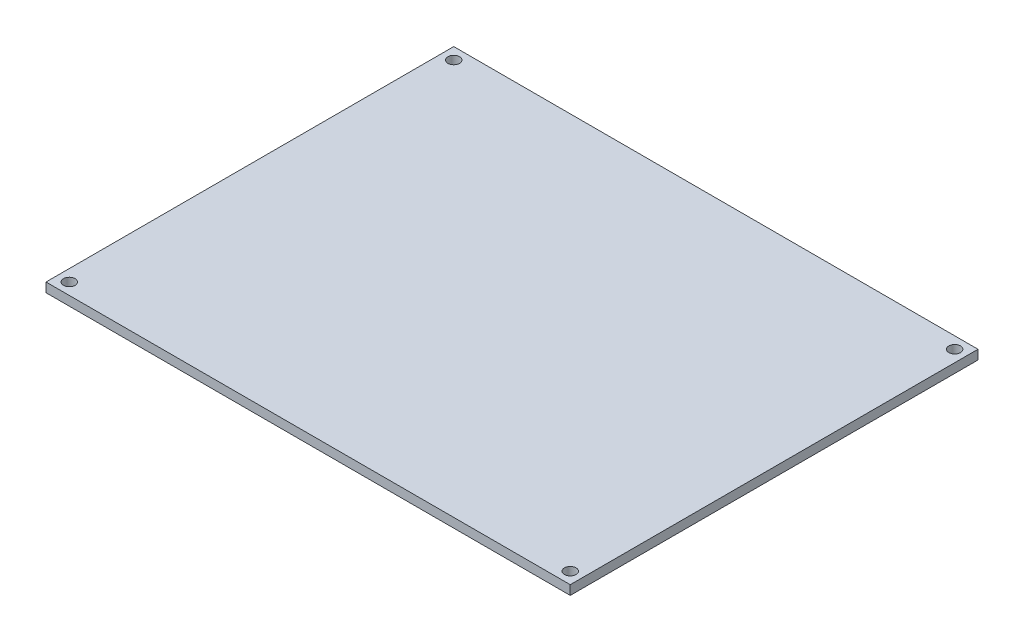
SolidWorks part; units mm, degrees
ref_plane "Front Plane" through (0, 0, 0) normal (0, 0, 1) x (1, 0, 0)
ref_plane "Top Plane" through (0, 0, 0) normal (0, 1, 0) x (1, 0, 0)
ref_plane "Right Plane" through (0, 0, 0) normal (1, 0, 0) x (0, 0, -1)
sketch "Sketch1" plane through (0, 0, 0) normal (0, 1, 0) x (1, 0, 0)
  line L5 (-45, -35) -> (45, -35)
  line L6 (-45, -35) -> (-45, 35)
  line L12 (-45, 35) -> (45, 35)
  line L13 (45, -35) -> (45, 35)
  line L14 (-45, -35) -> (45, 35) construction
  line L15 (-45, 35) -> (45, -35) construction
  line L16 (-43, -33) -> (43, -33) construction
  line L17 (-43, -33) -> (-43, 33) construction
  line L18 (-43, 33) -> (43, 33) construction
  line L19 (43, -33) -> (43, 33) construction
  line L20 (-43, -33) -> (43, 33) construction
  line L21 (-43, 33) -> (43, -33) construction
  circle A0 centre (-43, 33) radius 1
  circle A1 centre (43, 33) radius 1
  circle A2 centre (-43, -33) radius 1
  circle A3 centre (43, -33) radius 1
  point P0 (0, 0)
  point P6 (0, 0)
  dimension "D5" = 2
  dimension "D6" = 2
  dimension "D7" = 2
  dimension "D8" = 2
  dimension "D1" = 90
  dimension "D2" = 70
  dimension "D3" = 86
  dimension "D4" = 66
extrude "Boss-Extrude1" add sketch "Sketch1" along normal blind 1.6
